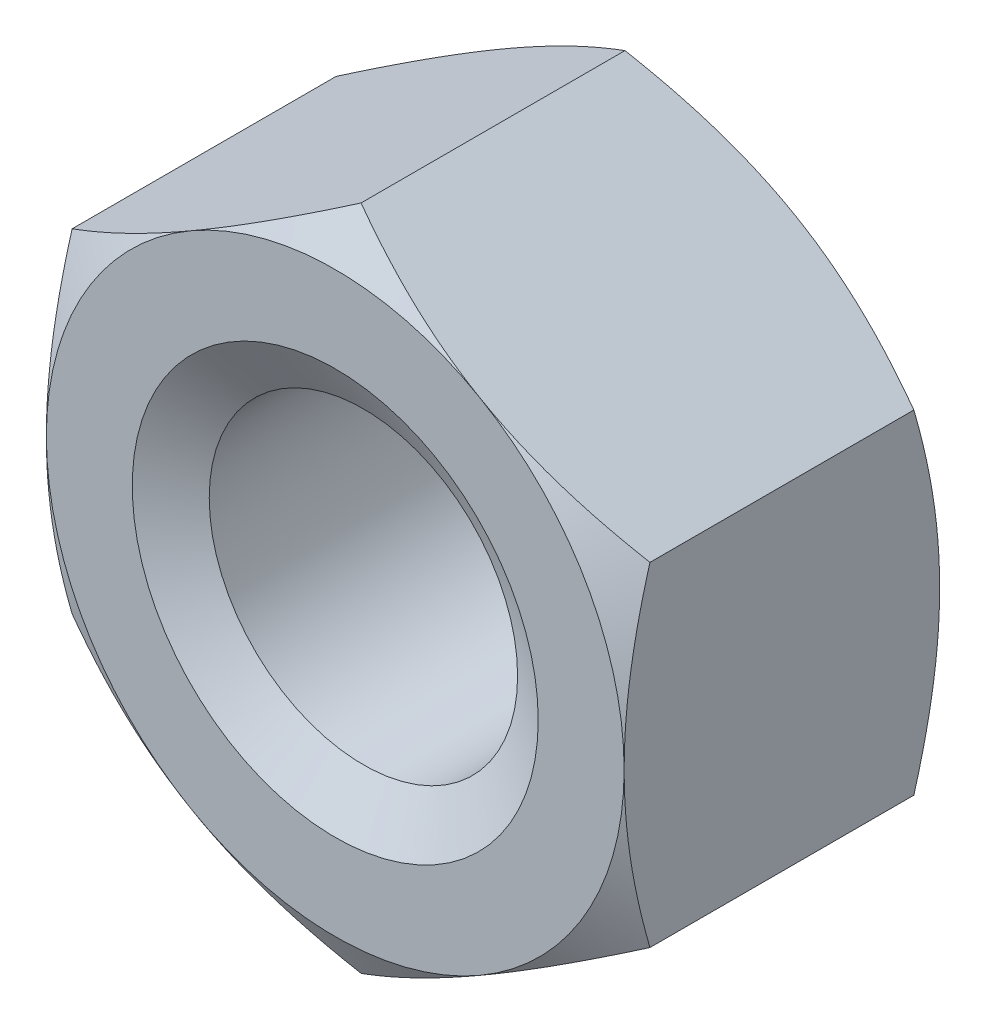
SolidWorks part; units mm, degrees
ref_plane "前视基准面" through (0, 0, 0) normal (0, 0, 1) x (1, 0, 0)
ref_plane "上视基准面" through (0, 0, 0) normal (0, 1, 0) x (1, 0, 0)
ref_plane "右视基准面" through (0, 0, 0) normal (1, 0, 0) x (0, 0, -1)
sketch "草图1" plane through (0, 0, 0) normal (1, 0, 0) x (0, 0, -1)
  line L0 (0, 7.19) -> (0, -7.19) construction
  line L1 (0, 0) -> (6.8, 0) construction
  line L2 (0, 0) -> (0, 7.19)
  line L3 (0, 7.19) -> (6.8, 7.19)
  line L4 (6.8, 7.19) -> (6.8, 0)
  line L5 (0, 4) -> (6.8, 4)
  line L6 (0, 3.3234) -> (6.8, 3.3234)
  line L7 (6.2, 7.19) -> (6.2, 0)
  line L8 (0, 6.5) -> (0.3984, 7.19)
  line L9 (0, 4) -> (0.3906, 3.3234)
  line L10 (0, -4) -> (0.3906, -3.3234)
  line L11 (6.2, 5.8) -> (6.8, 5.8)
  point P5 (1.6, 0)
  point P10 (5.55, 0)
  point P22 (0, 8.75)
  dimension "e" = 14.38
  dimension "m" = 6.8
  dimension "mw" = 5.2
  dimension "D" = 8
  dimension "P" = 1.25
  dimension "D81" = 6.6469
  dimension "c" = 0.6
  dimension "β" = 30
  dimension "s" = 13
  dimension "θ" = 120
  dimension "dw" = 11.6
  dimension "da" = 8.75
sketch "草图2" plane through (0, 0, 0) normal (0, 0, 1) x (1, 0, 0)
  line L1 (0, 7.19) -> (-6.2267, 3.595)
  line L2 (-6.2267, 3.595) -> (-6.2267, -3.595)
  line L3 (-6.2267, -3.595) -> (0, -7.19)
  line L4 (0, -7.19) -> (6.2267, -3.595)
  line L5 (6.2267, -3.595) -> (6.2267, 3.595)
  line L6 (6.2267, 3.595) -> (0, 7.19)
  circle A0 centre (0, 0) radius 6.2267 construction
  circle A1 centre (0, 0) radius 3.3234
sketch "草图3" plane through (0, 0, 0) normal (0, 0, 1) x (1, 0, 0)
  line L0 (0, 7.19) -> (-6.2267, 3.595) construction
  line L1 (6.2267, 3.595) -> (0, 7.19) construction
  line L2 (6.2267, -3.595) -> (6.2267, 3.595) construction
  line L3 (0, -7.19) -> (6.2267, -3.595) construction
  line L4 (-6.2267, -3.595) -> (0, -7.19) construction
  line L5 (-6.2267, 3.595) -> (-6.2267, -3.595) construction
  line L6 (0, 7.19) -> (-6.2267, 3.595)
  line L7 (6.2267, 3.595) -> (0, 7.19)
  line L8 (6.2267, -3.595) -> (6.2267, 3.595)
  line L9 (0, -7.19) -> (6.2267, -3.595)
  line L10 (-6.2267, -3.595) -> (0, -7.19)
  line L11 (-6.2267, 3.595) -> (-6.2267, -3.595)
  circle A0 centre (0, 0) radius 3.3234 construction
  circle A1 centre (0, 0) radius 3.3234
extrude "凸台-拉伸1" add sketch "草图3" against normal up to vertex (6.8 mm away) up to point (0, 0, -6.8)
cosmetic thread "装饰螺纹线1" parameters "D2"=8
sketch "草图4" plane through (0, 0, 0) normal (1, 0, 0) x (0, 0, -1)
  line L1 (0, 4.375) -> (0.6071, 3.3234)
  line L2 (0, 0) -> (6.8, 0) construction
  line L3 (0, 0) -> (6.8, 0) construction
  line L4 (3.4, 0) -> (3.4, 7.19) construction
  line L5 (0, 7.19) -> (6.8, 7.19) construction
  line L6 (0.6071, 3.3234) -> (0.6071, 0)
  line L7 (0.6071, 0) -> (0, 0)
  line L8 (0, 0) -> (0, 4.375)
  line L9 (6.8, 0) -> (6.8, 4.375)
  line L10 (6.1929, 0) -> (6.8, 0)
  line L11 (6.1929, 3.3234) -> (6.1929, 0)
  line L12 (6.8, 4.375) -> (6.1929, 3.3234)
  line L16 (0, 4) -> (0.3906, 3.3234) construction
  line L17 (0, 3.3234) -> (6.8, 3.3234) construction
  dimension "D1" = 8.75
revolve "切除-旋转1" cut sketch "草图4" angle 360 mid plane about L3
sketch "草图5" plane through (0, 0, 0) normal (0, 0, 1) x (1, 0, 0)
  circle A0 centre (0, 0) radius 6.2267
  circle A1 centre (0, 0) radius 10.785
  circle A2 centre (0, 0) radius 6.2267 construction
  dimension "D1" = 21.57
extrude "切除-拉伸1" cut sketch "草图5" against normal blind 1.36 draft 60
sketch "草图7" plane through (0, 0, -6.8) normal (0, 0, -1) x (-1, 0, 0)
  circle A1 centre (0, 0) radius 10.785
  circle A2 centre (0, 0) radius 10.785
  circle A3 centre (0, 0) radius 6.2267
  circle A4 centre (0, 0) radius 6.2267
  dimension "D1" = 0
  dimension "D2" = 0
extrude "切除-拉伸2" cut sketch "草图7" against normal blind 1.36 draft 60
sketch "草图6" [suppressed] plane through (0, 0, 0) normal (1, 0, 0) x (0, 0, -1)
  line L0 (1.3, 1.2) -> (1.1, 1.2)
  line L1 (1.1, 1.2) -> (1.1, 1.705)
  line L2 (1.1, 1.705) -> (1.3, 1.705)
  line L3 (1.3, 1.705) -> (1.3, 1.2)
  line L4 (0, 0) -> (1.3, 0) construction
  line L5 (0, 0) -> (1.3, 0) construction
revolve "切除-旋转2" [suppressed] cut sketch "草图6" angle 360 mid plane about L5
